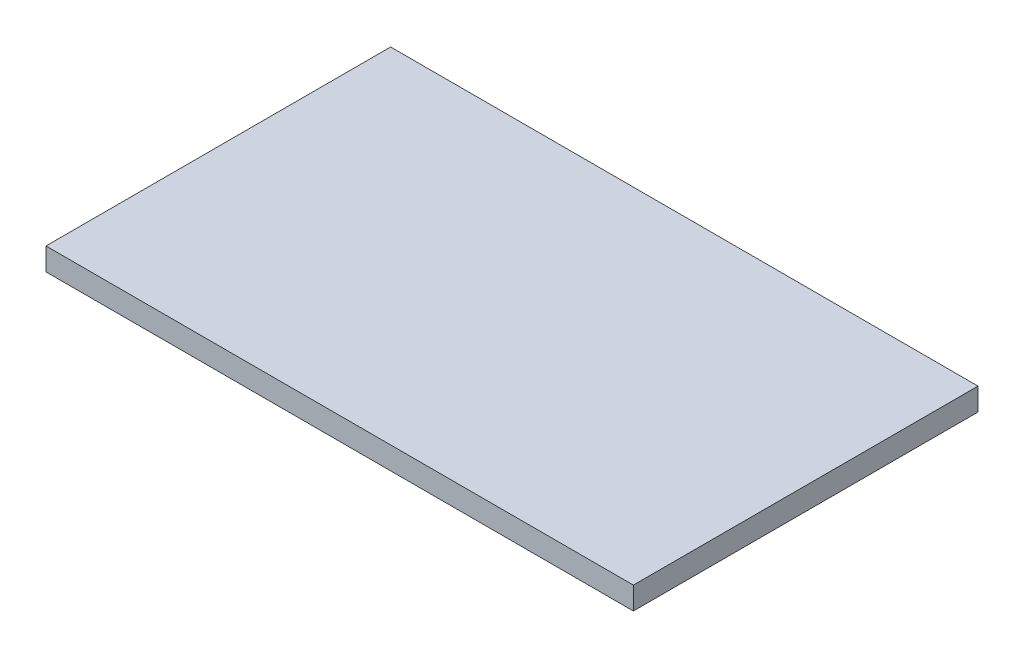
SolidWorks part; units mm, degrees
ref_plane "前基準面" through (0, 0, 0) normal (0, 0, 1) x (1, 0, 0)
ref_plane "上基準面" through (0, 0, 0) normal (0, 1, 0) x (1, 0, 0)
ref_plane "右基準面" through (0, 0, 0) normal (1, 0, 0) x (0, 0, -1)
sketch "草圖1" plane through (0, 0, 0) normal (0, 1, 0) x (1, 0, 0)
  line L1 (-39.2, 23) -> (39.2, 23)
  line L2 (-39.2, 23) -> (-39.2, -23)
  line L3 (-39.2, -23) -> (39.2, -23)
  line L4 (39.2, 23) -> (39.2, -23)
  line L5 (-39.2, 23) -> (39.2, -23) construction
  line L6 (-39.2, -23) -> (39.2, 23) construction
  point P0 (0, 0)
  dimension "D1" = 78.4
  dimension "D2" = 46
extrude "填料-伸長1" add sketch "草圖1" along normal blind 3
